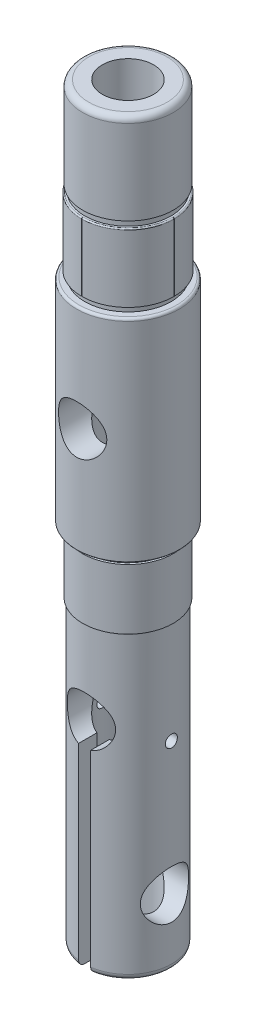
SolidWorks part; units mm, degrees
ref_plane "Front Plane" through (0, 0, 0) normal (0, 0, 1) x (1, 0, 0)
ref_plane "Top Plane" through (0, 0, 0) normal (0, 1, 0) x (1, 0, 0)
ref_plane "Right Plane" through (0, 0, 0) normal (1, 0, 0) x (0, 0, -1)
sketch "Sketch3" plane through (0, 0, 0) normal (0, 0, 1) x (1, 0, 0)
  line L0 (0, 68.7348) -> (0, -82.4457) construction
  line L1 (0, 0) -> (0, 124.3)
  line L2 (0, 124.3) -> (-6.5, 124.3)
  line L3 (-7.5, 123.3) -> (-7.5, 109.3)
  line L4 (-7.5, 109.3) -> (-7.15, 109.3)
  line L5 (-7.15, 109.3) -> (-7.15, 108.3)
  line L6 (-7.15, 108.3) -> (-7.45, 108.3)
  line L7 (-7.65, 108.1) -> (-7.65, 97)
  line L8 (-7.65, 97) -> (-7.15, 97)
  line L9 (-7.15, 97) -> (-7.15, 96)
  line L10 (-7.15, 96) -> (-8.1, 96)
  line L11 (-8.5, 95.6) -> (-8.5, 61.1)
  line L12 (-8.4, 61) -> (-7.35, 61)
  line L13 (-7.15, 60.8) -> (-7.15, 60)
  line L14 (-7.15, 60) -> (-7.5, 60)
  line L15 (-7.5, 60) -> (-7.5, 50)
  line L16 (-7.5, 50) -> (-7.45, 50)
  line L17 (-7.25, 49.8) -> (-7.25, 1)
  line L18 (-6.25, 0) -> (0, 0)
  arc A0 (-7.5, 123.3) -> (-6.5, 124.3) centre (-6.5, 123.3) cw
  arc A1 (-7.65, 108.1) -> (-7.45, 108.3) centre (-7.45, 108.1) cw
  arc A2 (-8.5, 95.6) -> (-8.1, 96) centre (-8.1, 95.6) cw
  arc A3 (-8.5, 61.1) -> (-8.4, 61) centre (-8.4, 61.1) ccw
  arc A4 (-7.45, 50) -> (-7.25, 49.8) centre (-7.45, 49.8) cw
  arc A5 (-7.15, 60.8) -> (-7.35, 61) centre (-7.35, 60.8) ccw
  arc A6 (-6.25, 0) -> (-7.25, 1) centre (-6.25, 1) cw
  point P12 (-7.15, 60.4)
  point P25 (-7.5, 124.3)
  point P28 (-7.65, 108.3)
  point P31 (-8.5, 96)
  point P34 (-8.5, 61)
  point P39 (-7.15, 61)
  dimension "D17" = 1
  dimension "D18" = 0.2
  dimension "D19" = 0.4
  dimension "D20" = 0.1
  dimension "D21" = 0.2
  dimension "D22" = 0.2
  dimension "D23" = 1
  dimension "D1" = 124.3
  dimension "D2" = 7.5
  dimension "D3" = 15
  dimension "D4" = 11.3
  dimension "D5" = 1
  dimension "D6" = 1
  dimension "D7" = 35
  dimension "D8" = 1
  dimension "D9" = 10
  dimension "D10" = 7.15
  dimension "D11" = 7.15
  dimension "D12" = 7.15
  dimension "D13" = 7.25
  dimension "D14" = 7.5
  dimension "D15" = 8.5
  dimension "D16" = 7.65
revolve "Revolve1" add sketch "Sketch3" angle 360 about L0
sketch "Sketch4" plane through (0, 124.3, 0) normal (0, 1, 0) x (1, 0, 0)
  circle A0 centre (0, 0) radius 4.25
  dimension "D1" = 8.5
extrude "Cut-Extrude1" cut sketch "Sketch4" against normal through all
sketch "Sketch5" plane through (0, 0, 0) normal (0, 0, 1) x (1, 0, 0)
  line L1 (-8.5, 95.6) -> (8.5, 95.6)
  line L2 (-8.5, 95.6) -> (-8.5, 61.1)
  line L3 (-8.5, 61.1) -> (8.5, 61.1)
  line L4 (8.5, 95.6) -> (8.5, 61.1)
  line L5 (-8.5, 95.6) -> (8.5, 61.1) construction
  line L6 (-8.5, 61.1) -> (8.5, 95.6) construction
  circle A0 centre (0, 78.35) radius 4
  point P4 (0, 78.35)
  dimension "D1" = 8
extrude "Cut-Extrude2" cut sketch "Sketch5" along normal through all contours A0
sketch "Sketch7" plane through (0, 0, 0) normal (0, 0, 1) x (1, 0, 0)
  line L0 (0, 0) -> (0, 36) construction
  line L1 (-7.25, 49.8) -> (7.25, 49.8) construction
  line L2 (-7.25, 49.8) -> (-7.25, 1) construction
  line L4 (7.25, 49.8) -> (7.25, 1) construction
  line L5 (-7.25, 49.8) -> (7.25, 1) construction
  line L6 (-7.25, 1) -> (7.25, 49.8) construction
  line L7 (0, 0) -> (-1, 0)
  line L8 (-1, 0) -> (-1, 32.127)
  line L9 (0, 0) -> (1, 0)
  line L10 (-7.25, 0) -> (7.25, 0) construction
  line L11 (1, 0) -> (1, 32.127)
  arc A0 (1, 32.127) -> (-1, 32.127) centre (0, 36) ccw
  point P4 (0, 25.4)
  dimension "D2" = 8
  dimension "D1" = 36
  dimension "D3" = 1
  dimension "D4" = 1
extrude "Cut-Extrude3" cut sketch "Sketch7" along normal through all contours A0 L8 L7 L9 L11
sketch "Sketch8" plane through (0, 0, 0) normal (1, 0, 0) x (0, 0, -1)
  line L0 (0, 0) -> (0, 11) construction
  line L1 (0, 0) -> (0, 33) construction
  circle A0 centre (0, 11) radius 4
  circle A1 centre (0, 33) radius 1
  dimension "D2" = 8
  dimension "D4" = 2
  dimension "D1" = 11
  dimension "D3" = 33
extrude "Cut-Extrude4" cut sketch "Sketch8" against normal through all both and the other way through all
sketch "Sketch9" plane through (0, 0, 0) normal (0, 0, 1) x (1, 0, 0)
  circle A0 centre (0, 36) radius 0.75
  dimension "D1" = 1.5
extrude "Cut-Extrude5" cut sketch "Sketch9" against normal through all
ref_plane "Plane1" through (0, 108.3, 0) normal (0, 1, 0) x (1, 0, 0)
sketch "Sketch10" plane through (0, 108.3, 0) normal (0, 1, 0) x (1, 0, 0)
  line L0 (0, 0) -> (-7.65, 0) construction
  line L1 (0, 0) -> (0, 7.65) construction
  line L2 (0, 0) -> (-7.6499, 0.0334)
  line L3 (0, 0) -> (0.0334, 7.6499)
  line L4 (0, 0) -> (-7.6499, -0.0334)
  line L5 (0, 0) -> (-0.0334, 7.6499)
  line L6 (0, 0) -> (7.6499, -0.0334)
  line L7 (0, 0) -> (7.6499, 0.0334)
  line L8 (0, 0) -> (-0.0334, -7.6499)
  line L9 (0, 0) -> (0.0334, -7.6499)
  arc A0 (-7.6499, 0.0334) -> (-7.6499, -0.0334) centre (0, 0) ccw
  arc A1 (-0.0334, -7.6499) -> (0.0334, -7.6499) centre (0, 0) ccw
  arc A2 (7.6499, -0.0334) -> (7.6499, 0.0334) centre (0, 0) ccw
  arc A3 (0.0334, 7.6499) -> (-0.0334, 7.6499) centre (0, 0) ccw
  arc A4 (-7.4999, 0.0327) -> (-7.4999, -0.0327) centre (0, 0) ccw
  arc A5 (0.0327, 7.4999) -> (-0.0327, 7.4999) centre (0, 0) ccw
  arc A6 (-0.0327, -7.4999) -> (0.0327, -7.4999) centre (0, 0) ccw
  arc A7 (7.4999, -0.0327) -> (7.4999, 0.0327) centre (0, 0) ccw
  dimension "D1" = 15.3
  dimension "D4" = 15
  dimension "D2" = 0.25
  dimension "D3" = 0.25
extrude "Cut-Extrude6" cut sketch "Sketch10" against normal blind 11.3 contours A5 L3 A3 L5 | A7 L6 A2 L7 | A6 L8 A1 L9 | A4 L2 A0 L4
